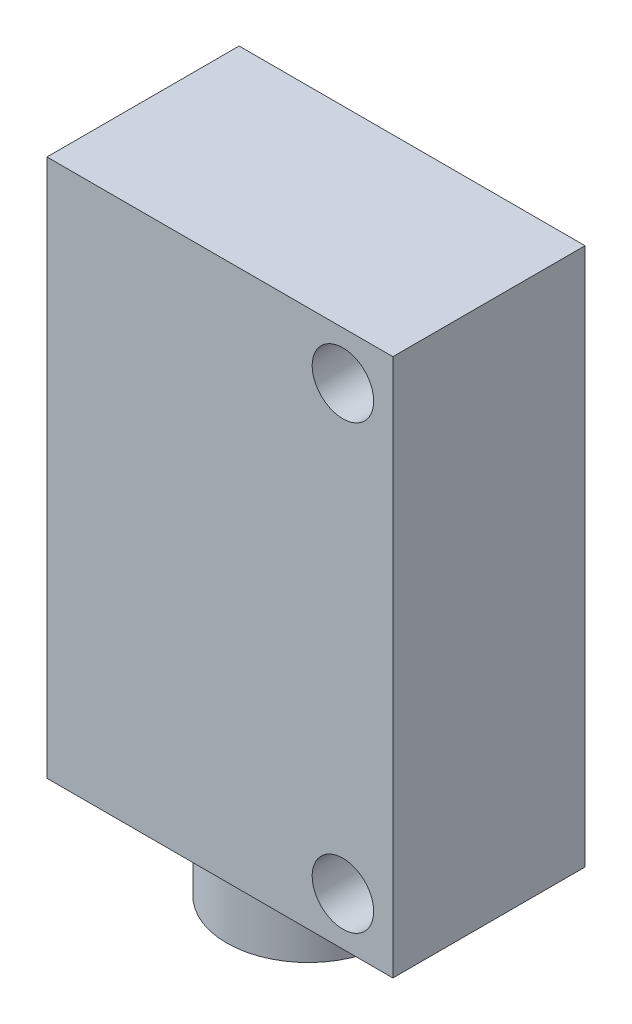
SolidWorks part; units mm, degrees
ref_plane "Plan de face" through (0, 0, 0) normal (0, 0, 1) x (1, 0, 0)
ref_plane "Plan de dessus" through (0, 0, 0) normal (0, 1, 0) x (1, 0, 0)
ref_plane "Plan de droite" through (0, 0, 0) normal (1, 0, 0) x (0, 0, -1)
sketch "Esquisse1" plane through (0, 0, 0) normal (0, 0, 1) x (1, 0, 0)
  line L1 (0, 0) -> (18, 0)
  line L2 (0, 0) -> (0, 28)
  line L3 (0, 28) -> (18, 28)
  line L4 (18, 0) -> (18, 28)
extrude "Boss.-Extru.1" add sketch "Esquisse1" along normal blind 10
sketch "Esquisse3" plane through (0, 0, 0) normal (0, -1, 0) x (1, 0, 0)
  circle A0 centre (8.6, 5) radius 4.25
extrude "Boss.-Extru.2" add sketch "Esquisse3" along normal blind 3.5 contours A0
sketch "Esquisse4" plane through (0, 0, 0) normal (0, 0, -1) x (-1, 0, 0)
  circle A0 centre (-15.4, 25.5) radius 1.6
extrude "Enlèv. mat.-Extru.1" cut sketch "Esquisse4" against normal blind 10.2
sketch "Esquisse5" plane through (0, 0, 0) normal (0, 0, -1) x (-1, 0, 0)
  circle A0 centre (-15.4, 2.5) radius 1.6
extrude "Enlèv. mat.-Extru.2" cut sketch "Esquisse5" against normal blind 10.2
sketch "Esquisse6" plane through (0, 0, 0) normal (-1, 0, 0) x (0, 0, 1)
  line L1 (1.7369, 25.6158) -> (8.6193, 25.6158)
  line L2 (1.7369, 25.6158) -> (1.7369, 2.1259)
  line L3 (1.7369, 2.1259) -> (8.6193, 2.1259)
  line L4 (8.6193, 25.6158) -> (8.6193, 2.1259)
extrude "Boss.-Extru.3" add sketch "Esquisse6" along normal blind 1
